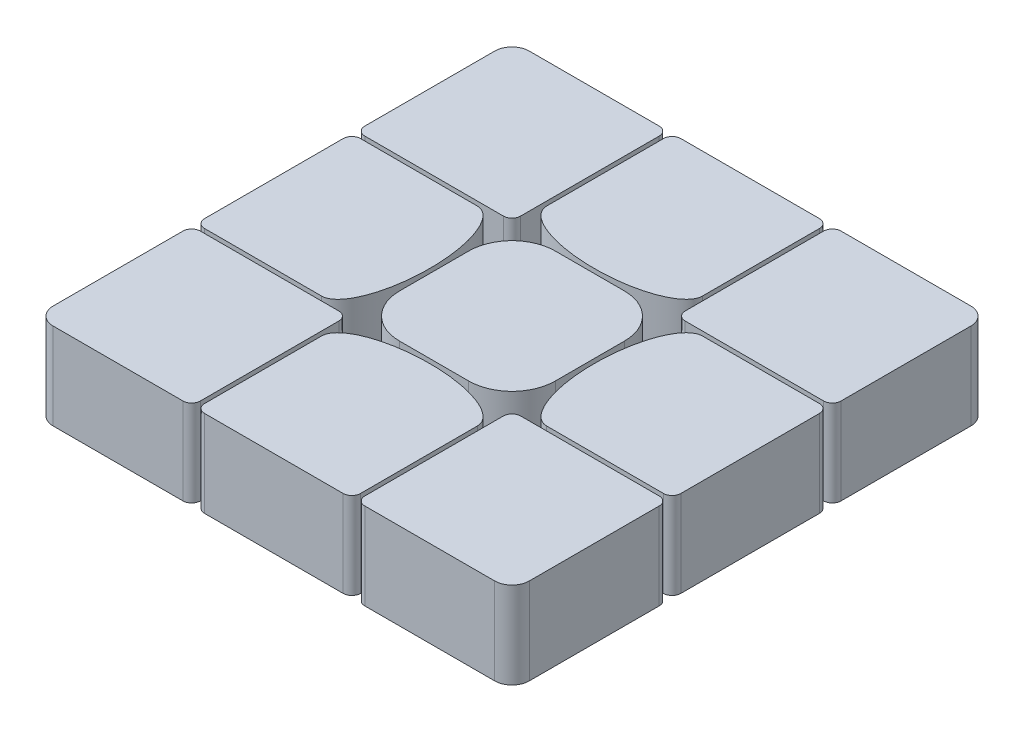
SolidWorks part; units mm, degrees
ref_plane "Front Plane" through (0, 0, 0) normal (0, 0, 1) x (1, 0, 0)
ref_plane "Top Plane" through (0, 0, 0) normal (0, 1, 0) x (1, 0, 0)
ref_plane "Right Plane" through (0, 0, 0) normal (1, 0, 0) x (0, 0, -1)
sketch "Sketch2" plane through (0, 0, 0) normal (0, 1, 0) x (1, 0, 0)
  line L0 (80.1052, 19.7039) -> (95.1052, 19.7039)
  line L1 (96.6052, -3.7961) -> (96.6052, -11.7961)
  line L2 (79.1052, 1.2039) -> (92.6052, 1.2039)
  line L3 (96.1052, 18.7039) -> (96.1052, 2.7039)
  line L4 (97.6052, 19.7039) -> (113.6052, 19.7039)
  line L5 (96.6052, 18.7039) -> (96.6052, 5.2039)
  line L6 (78.1052, 0.2039) -> (78.1052, -15.7961)
  line L7 (101.6052, 1.2039) -> (109.6052, 1.2039)
  line L8 (79.1052, 1.7039) -> (95.1052, 1.7039)
  line L9 (78.1052, 17.7039) -> (78.1052, 2.7039)
  line L10 (133.1052, 17.7039) -> (133.1052, 2.7039)
  line L11 (132.1052, 1.7039) -> (116.1052, 1.7039)
  line L12 (133.1052, 0.2039) -> (133.1052, -15.7961)
  line L13 (114.6052, 18.7039) -> (114.6052, 5.2039)
  line L14 (115.1052, 18.7039) -> (115.1052, 2.7039)
  line L15 (132.1052, 1.2039) -> (118.6052, 1.2039)
  line L16 (114.6052, -3.7961) -> (114.6052, -11.7961)
  line L17 (131.1052, 19.7039) -> (116.1052, 19.7039)
  line L18 (131.1052, -35.2961) -> (116.1052, -35.2961)
  line L19 (132.1052, -16.7961) -> (118.6052, -16.7961)
  line L20 (115.1052, -34.2961) -> (115.1052, -18.2961)
  line L21 (114.6052, -34.2961) -> (114.6052, -20.7961)
  line L22 (132.1052, -17.2961) -> (116.1052, -17.2961)
  line L23 (133.1052, -33.2961) -> (133.1052, -18.2961)
  line L24 (78.1052, -33.2961) -> (78.1052, -18.2961)
  line L25 (79.1052, -17.2961) -> (95.1052, -17.2961)
  line L26 (101.6052, -16.7961) -> (109.6052, -16.7961)
  line L27 (96.6052, -34.2961) -> (96.6052, -20.7961)
  line L28 (97.6052, -35.2961) -> (113.6052, -35.2961)
  line L29 (96.1052, -34.2961) -> (96.1052, -18.2961)
  line L30 (79.1052, -16.7961) -> (92.6052, -16.7961)
  line L31 (80.1052, -35.2961) -> (95.1052, -35.2961)
  arc A0 (80.1052, 19.7039) -> (78.1052, 17.7039) centre (80.1052, 17.7039) ccw
  arc A1 (78.1052, 0.2039) -> (79.1052, 1.2039) centre (79.1052, 0.2039) cw
  arc A2 (95.1052, 19.7039) -> (96.1052, 18.7039) centre (95.1052, 18.7039) cw
  arc A3 (95.1052, 1.7039) -> (96.1052, 2.7039) centre (95.1052, 2.7039) ccw
  arc A4 (97.6052, 19.7039) -> (96.6052, 18.7039) centre (97.6052, 18.7039) ccw
  arc A5 (101.6052, 1.2039) -> (96.6052, -3.7961) centre (101.6052, -3.7961) ccw
  arc A6 (78.1052, 2.7039) -> (79.1052, 1.7039) centre (79.1052, 2.7039) ccw
  arc A7 (133.1052, 2.7039) -> (132.1052, 1.7039) centre (132.1052, 2.7039) cw
  arc A8 (109.6052, 1.2039) -> (114.6052, -3.7961) centre (109.6052, -3.7961) cw
  arc A9 (113.6052, 19.7039) -> (114.6052, 18.7039) centre (113.6052, 18.7039) cw
  arc A10 (116.1052, 1.7039) -> (115.1052, 2.7039) centre (116.1052, 2.7039) cw
  arc A11 (116.1052, 19.7039) -> (115.1052, 18.7039) centre (116.1052, 18.7039) ccw
  arc A12 (133.1052, 0.2039) -> (132.1052, 1.2039) centre (132.1052, 0.2039) ccw
  arc A13 (131.1052, 19.7039) -> (133.1052, 17.7039) centre (131.1052, 17.7039) cw
  arc A14 (131.1052, -35.2961) -> (133.1052, -33.2961) centre (131.1052, -33.2961) ccw
  arc A15 (133.1052, -15.7961) -> (132.1052, -16.7961) centre (132.1052, -15.7961) cw
  arc A16 (116.1052, -35.2961) -> (115.1052, -34.2961) centre (116.1052, -34.2961) cw
  arc A17 (116.1052, -17.2961) -> (115.1052, -18.2961) centre (116.1052, -18.2961) ccw
  arc A18 (113.6052, -35.2961) -> (114.6052, -34.2961) centre (113.6052, -34.2961) ccw
  arc A19 (109.6052, -16.7961) -> (114.6052, -11.7961) centre (109.6052, -11.7961) ccw
  arc A20 (133.1052, -18.2961) -> (132.1052, -17.2961) centre (132.1052, -18.2961) ccw
  arc A21 (78.1052, -18.2961) -> (79.1052, -17.2961) centre (79.1052, -18.2961) cw
  arc A22 (101.6052, -16.7961) -> (96.6052, -11.7961) centre (101.6052, -11.7961) cw
  arc A23 (97.6052, -35.2961) -> (96.6052, -34.2961) centre (97.6052, -34.2961) cw
  arc A24 (95.1052, -17.2961) -> (96.1052, -18.2961) centre (95.1052, -18.2961) cw
  arc A25 (95.1052, -35.2961) -> (96.1052, -34.2961) centre (95.1052, -34.2961) ccw
  arc A26 (78.1052, -15.7961) -> (79.1052, -16.7961) centre (79.1052, -15.7961) ccw
  arc A27 (80.1052, -35.2961) -> (78.1052, -33.2961) centre (80.1052, -33.2961) cw
  ellipse E0 centre (105.6052, 5.2039) end of major axis (96.6052, 5.2039) minor radius 3.5 (96.6052, 5.2039) -> (114.6052, 5.2039) ccw
  ellipse E1 centre (92.6052, -7.7961) end of major axis (92.6052, 1.2039) minor radius 3.5 (92.6052, 1.2039) -> (92.6052, -16.7961) cw
  ellipse E2 centre (118.6052, -7.7961) end of major axis (118.6052, 1.2039) minor radius 3.5 (118.6052, 1.2039) -> (118.6052, -16.7961) ccw
  ellipse E3 centre (105.6052, -20.7961) end of major axis (96.6052, -20.7961) minor radius 3.5 (96.6052, -20.7961) -> (114.6052, -20.7961) cw
extrude "Boss-Extrude1" add sketch "Sketch2" along normal blind 10
